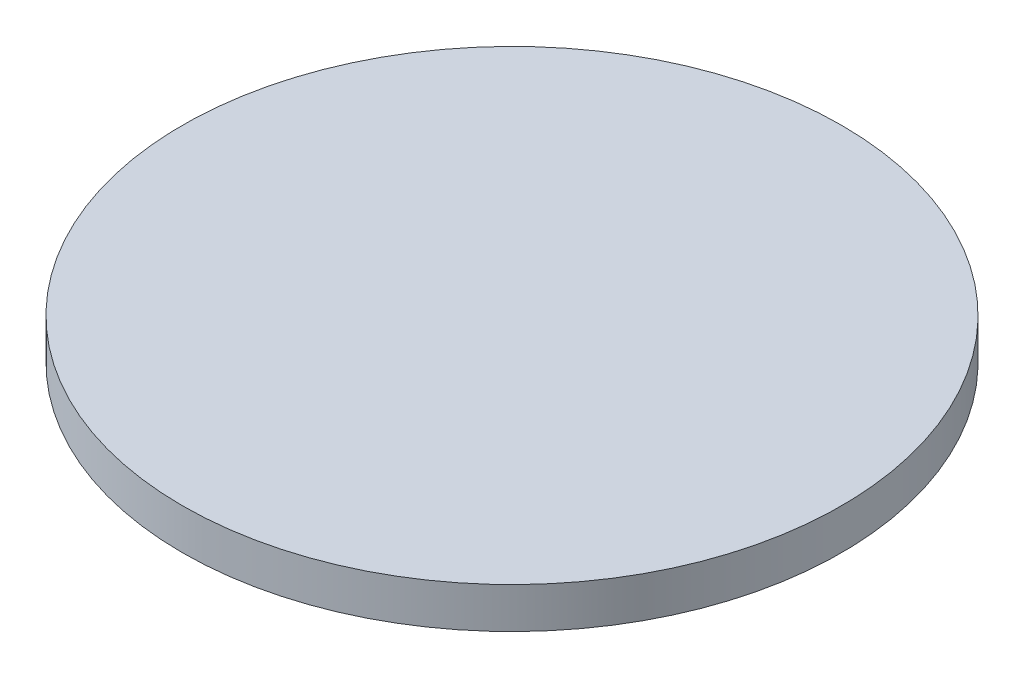
SolidWorks part; units mm, degrees
ref_plane "Front Plane" through (0, 0, 0) normal (0, 0, 1) x (1, 0, 0)
ref_plane "Top Plane" through (0, 0, 0) normal (0, 1, 0) x (1, 0, 0)
ref_plane "Right Plane" through (0, 0, 0) normal (1, 0, 0) x (0, 0, -1)
sketch "Sketch1" plane through (0, 0, 0) normal (0, 1, 0) x (1, 0, 0)
  circle A0 centre (0, 0) radius 19.2786
  dimension "D1" = 38.5572
extrude "Boss-Extrude1" add sketch "Sketch1" along normal blind 2.3813
